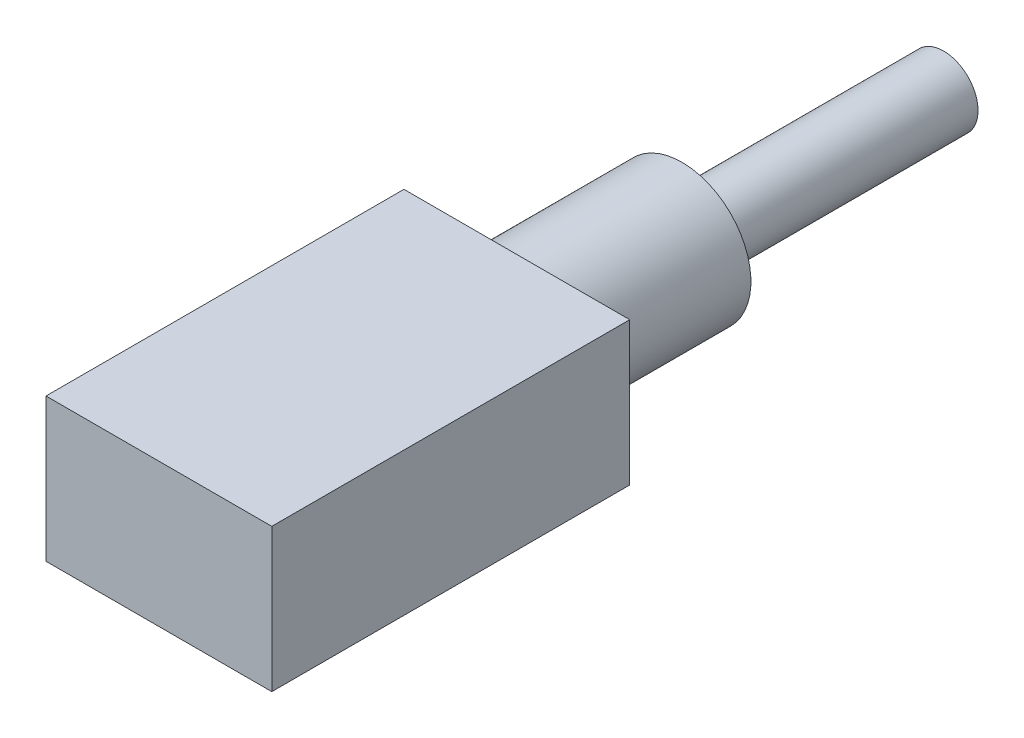
SolidWorks part; units mm, degrees
ref_plane "前基準面" through (0, 0, 0) normal (0, 0, 1) x (1, 0, 0)
ref_plane "上基準面" through (0, 0, 0) normal (0, 1, 0) x (1, 0, 0)
ref_plane "右基準面" through (0, 0, 0) normal (1, 0, 0) x (0, 0, -1)
sketch "草圖1" plane through (0, 0, 0) normal (0, 0, 1) x (1, 0, 0)
  line L0 (-43.8655, -29.1074) -> (43.7345, -29.1074) construction
  line L1 (-34.3655, -49.3074) -> (-42.5655, -49.3074)
  line L2 (-34.3655, -49.3074) -> (-34.3655, -44.1074)
  line L3 (-34.3655, -44.1074) -> (-42.5655, -44.1074)
  line L4 (-42.5655, -49.3074) -> (-42.5655, -44.1074)
  line L5 (-44.5655, -42.9237) -> (-44.5655, -29.8074) construction
  dimension "D1" = 5.2
  dimension "D2" = 8.2
  dimension "D3" = 15
  dimension "D4" = 2
extrude "填料-伸長1" add sketch "草圖1" along normal blind 13
sketch "草圖2" plane through (0, 0, 0) normal (0, 0, -1) x (-1, 0, 0)
  line L0 (42.5655, -44.1074) -> (42.5655, -49.3074) construction
  line L1 (34.3655, -44.1074) -> (42.5655, -44.1074) construction
  circle A0 centre (38.4655, -46.7074) radius 2.5
  dimension "D1" = 5
  dimension "D2" = 4.1
  dimension "D3" = 2.6
extrude "填料-伸長2" add sketch "草圖2" along normal blind 6
sketch "草圖3" plane through (0, 0, -6) normal (0, 0, -1) x (-1, 0, 0)
  circle A0 centre (38.4655, -46.7074) radius 1.25
  circle A1 centre (38.4655, -46.7074) radius 2.5 construction
  dimension "D1" = 2.5
extrude "填料-伸長3" add sketch "草圖3" along normal blind 9.5
